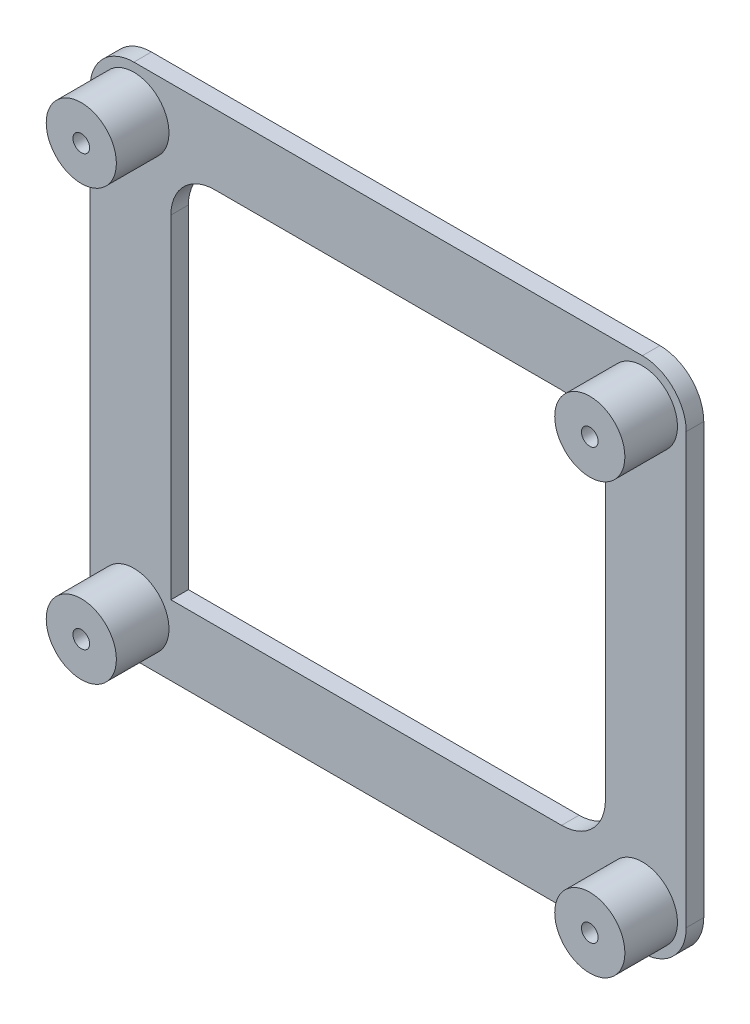
SolidWorks part; units mm, degrees
ref_plane "Front Plane" through (0, 0, 0) normal (0, 0, 1) x (1, 0, 0)
ref_plane "Top Plane" through (0, 0, 0) normal (0, 1, 0) x (1, 0, 0)
ref_plane "Right Plane" through (0, 0, 0) normal (1, 0, 0) x (0, 0, -1)
sketch "Sketch1" plane through (0, 0, 0) normal (0, 0, 1) x (1, 0, 0)
  line L1 (-29, -24.5) -> (29, -24.5) construction
  line L2 (-29, -24.5) -> (-29, 24.5) construction
  line L3 (-29, 24.5) -> (29, 24.5) construction
  line L4 (29, -24.5) -> (29, 24.5) construction
  line L5 (-29, -24.5) -> (29, 24.5) construction
  line L6 (-29, 24.5) -> (29, -24.5) construction
  line L7 (-34, -29.5) -> (34, -29.5)
  line L8 (-34, -29.5) -> (-34, 29.5)
  line L9 (-34, 29.5) -> (34, 29.5)
  line L10 (34, -29.5) -> (34, 29.5)
  line L11 (-34, -29.5) -> (34, 29.5) construction
  line L12 (-34, 29.5) -> (34, -29.5) construction
  line L13 (-24.7797, -21.5) -> (24.7797, -21.5)
  line L14 (-24.7797, -21.5) -> (-24.7797, 21.5)
  line L15 (-24.7797, 21.5) -> (24.7797, 21.5)
  line L16 (24.7797, -21.5) -> (24.7797, 21.5)
  line L17 (-24.7797, -21.5) -> (24.7797, 21.5) construction
  line L18 (-24.7797, 21.5) -> (24.7797, -21.5) construction
  circle A0 centre (-29, 24.5) radius 0.95
  circle A1 centre (29, 24.5) radius 0.95
  circle A2 centre (29, -24.5) radius 0.95
  circle A3 centre (-29, -24.5) radius 0.95
  point P0 (0, 0)
  point P6 (0, 0)
  point P11 (0, 0)
  dimension "D6" = 1.9
  dimension "D1" = 58
  dimension "D2" = 49
  dimension "D3" = 5
  dimension "D4" = 5
  dimension "D5" = 8
extrude "Boss-Extrude1" add sketch "Sketch1" along normal blind 2
sketch "Sketch2" plane through (0, 0, 2) normal (0, 0, 1) x (1, 0, 0)
  circle A0 centre (-29, 24.5) radius 4
  circle A1 centre (29, 24.5) radius 4
  circle A2 centre (29, -24.5) radius 4
  circle A3 centre (-29, -24.5) radius 4
  circle A4 centre (-29, -24.5) radius 0.95 construction
  circle A5 centre (29, -24.5) radius 0.95 construction
  circle A6 centre (29, 24.5) radius 0.95 construction
  circle A7 centre (-29, 24.5) radius 0.95 construction
  circle A8 centre (-29, -24.5) radius 0.95
  circle A9 centre (29, -24.5) radius 0.95
  circle A10 centre (29, 24.5) radius 0.95
  circle A11 centre (-29, 24.5) radius 0.95
  dimension "D1" = 8
extrude "Boss-Extrude2" add sketch "Sketch2" along normal blind 6
fillet "Fillet1" radius 5 7 edges at (24.7797, -21.5, 1) (24.7797, 21.5, 1) (-24.7797, 21.5, 1) (-34, 29.5, 1) (34, 29.5, 1) (34, -29.5, 1) (-34, -29.5, 1)
